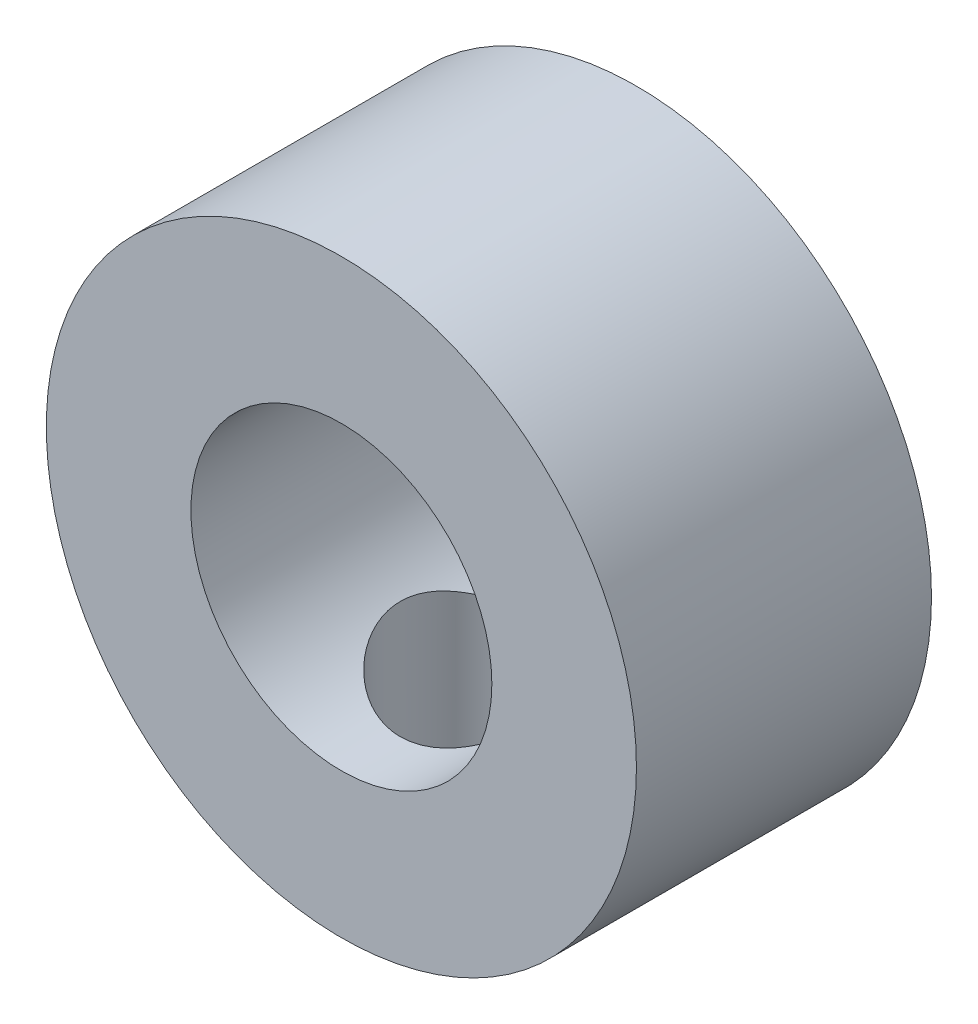
SolidWorks part; units mm, degrees
ref_plane "Спереди" through (0, 0, 0) normal (0, 0, 1) x (1, 0, 0)
ref_plane "Сверху" through (0, 0, 0) normal (0, 1, 0) x (1, 0, 0)
ref_plane "Справа" through (0, 0, 0) normal (1, 0, 0) x (0, 0, -1)
sketch "Эскиз1" plane through (0, 0, 0) normal (0, 0, 1) x (1, 0, 0)
  circle A0 centre (0, 0) radius 2.55
  circle A1 centre (0, 0) radius 5
  dimension "D1" = 5.1
  dimension "D2" = 10
extrude "Бобышка-Вытянуть1" add sketch "Эскиз1" along normal blind 5
sketch "Эскиз2" plane through (0, 0, 0) normal (0, 1, 0) x (1, 0, 0)
  line L0 (5, -5) -> (5, 0) construction
  line L1 (5, -5) -> (5, 0) construction
  circle A0 centre (0, -2.5) radius 1.5
  point P6 (5, -2.5)
  dimension "D1" = 3
extrude "Вырез-Вытянуть1" cut sketch "Эскиз2" against normal through all
